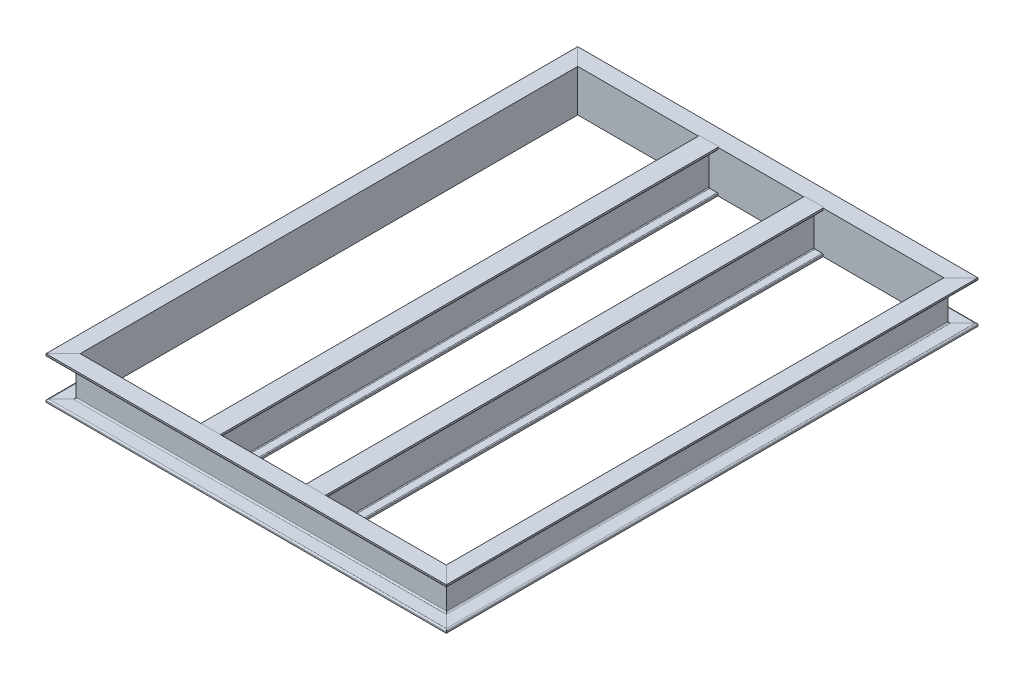
SolidWorks part; units mm, degrees
ref_plane "Alzado" through (0, 0, 0) normal (0, 0, 1) x (1, 0, 0)
ref_plane "Planta" through (0, 0, 0) normal (0, 1, 0) x (1, 0, 0)
ref_plane "Vista lateral" through (0, 0, 0) normal (1, 0, 0) x (0, 0, -1)
sketch "Croquis1" plane through (0, 0, 0) normal (0, 1, 0) x (1, 0, 0)
  line L0 (0, 1074.0986) -> (0, -1451.7808) construction
  line L1 (-700, -950) -> (700, -950)
  line L2 (-700, -950) -> (-700, 950)
  line L3 (-700, 950) -> (700, 950)
  line L4 (700, -950) -> (700, 950)
  line L5 (-700, -950) -> (700, 950) construction
  line L6 (-700, 950) -> (700, -950) construction
  line L7 (-200, 950) -> (-200, -950)
  line L8 (200, 950) -> (200, -950)
  line L9 (-700, 475) -> (700, 475) construction
  line L10 (-700, 0) -> (700, 0) construction
  line L11 (-700, -475) -> (700, -475) construction
  point P0 (0, 0)
  dimension "D1" = 1900
  dimension "D2" = 1400
  dimension "D3" = 200
  dimension "D4" = 475
  dimension "D5" = 3
other "Miembro estructural2"
ref_plane "Plano2" through (-700, 0, 950) normal (0, 0, -1) x (-1, 0, 0)
sketch "Croquis12" plane through (-700, 0, 950) normal (0, 0, -1) x (-1, 0, 0)
  line L0 (0, 94.8652) -> (0, -94.4803) construction
  line L1 (-161.6749, 0) -> (169.1749, 0) construction
  line L2 (-3.75, -80) -> (-3.75, 80)
  line L3 (-3.75, 80) -> (61.25, 80)
  line L4 (61.25, 80) -> (61.25, 75)
  line L5 (55.75, 69.5) -> (9.25, 69.5)
  line L6 (3.75, 64) -> (3.75, -64)
  line L7 (55.75, -69.5) -> (9.25, -69.5)
  line L8 (61.25, -80) -> (61.25, -75)
  line L9 (-3.75, -80) -> (61.25, -80)
  arc A0 (61.25, 75) -> (55.75, 69.5) centre (55.75, 75) cw
  arc A1 (9.25, 69.5) -> (3.75, 64) centre (9.25, 64) ccw
  arc A2 (9.25, -69.5) -> (3.75, -64) centre (9.25, -64) cw
  arc A3 (61.25, -75) -> (55.75, -69.5) centre (55.75, -75) ccw
  point P5 (0, 0)
  point P16 (3.75, 0)
  point P23 (-3.75, 0)
  dimension "D6" = 5.5
  dimension "D1" = 80
  dimension "D2" = 10.5
  dimension "D3" = 3.75
  dimension "D4" = 7.5
  dimension "D5" = 65
other "Miembro estructural4"
ref_plane "Plano4" through (-200, 0, -950) normal (0, 0, 1) x (1, 0, 0)
sketch "Croquis2" plane through (-200, 0, -950) normal (0, 0, 1) x (1, 0, 0)
  line L0 (0, 102.638) -> (0, -108.8585) construction
  line L1 (37, 80) -> (-37, 80)
  line L2 (-37, 80) -> (-37, 73.68)
  line L3 (-33.82, 70.5) -> (-6.35, 70.5)
  line L4 (-3.17, 67.32) -> (-3.17, -67.32)
  line L5 (-6.35, -70.5) -> (-33.82, -70.5)
  line L6 (-37, -73.68) -> (-37, -80)
  line L7 (-37, -80) -> (37, -80)
  line L8 (37, -73.68) -> (37, -80)
  line L9 (6.35, -70.5) -> (33.82, -70.5)
  line L10 (3.17, 67.32) -> (3.17, -67.32)
  line L11 (33.82, 70.5) -> (6.35, 70.5)
  line L12 (37, 80) -> (37, 73.68)
  arc A0 (-33.82, -70.5) -> (-37, -73.68) centre (-33.82, -73.68) ccw
  arc A1 (-3.17, -67.32) -> (-6.35, -70.5) centre (-6.35, -67.32) cw
  arc A2 (-6.35, 70.5) -> (-3.17, 67.32) centre (-6.35, 67.32) cw
  arc A3 (-37, 73.68) -> (-33.82, 70.5) centre (-33.82, 73.68) ccw
  arc A4 (33.82, -70.5) -> (37, -73.68) centre (33.82, -73.68) cw
  arc A5 (3.17, -67.32) -> (6.35, -70.5) centre (6.35, -67.32) ccw
  arc A6 (6.35, 70.5) -> (3.17, 67.32) centre (6.35, 67.32) ccw
  arc A7 (37, 73.68) -> (33.82, 70.5) centre (33.82, 73.68) cw
  point P3 (0, 0)
  point P13 (-37, -70.5)
  point P21 (0, -80)
  point P34 (0, 80)
  dimension "D6" = 3.18
  dimension "D1" = 160
  dimension "D2" = 80
  dimension "D3" = 37
  dimension "D4" = 3.17
  dimension "D5" = 9.5
